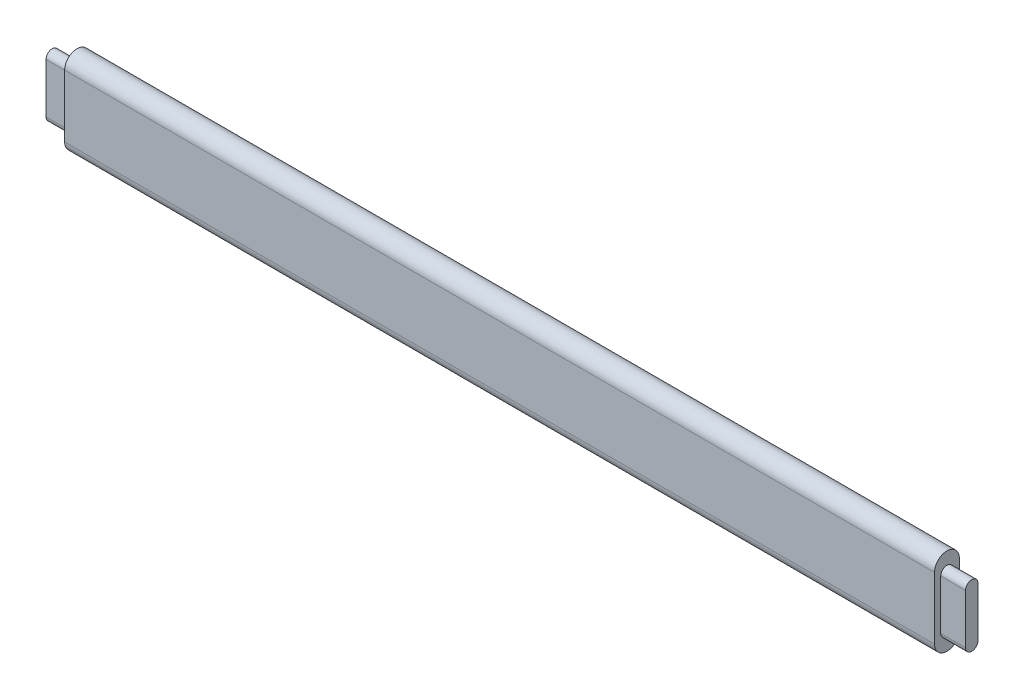
SolidWorks part; units mm, degrees
ref_plane "Front Plane" through (0, 0, 0) normal (0, 0, 1) x (1, 0, 0)
ref_plane "Top Plane" through (0, 0, 0) normal (0, 1, 0) x (1, 0, 0)
ref_plane "Right Plane" through (0, 0, 0) normal (1, 0, 0) x (0, 0, -1)
sketch "Sketch1" plane through (0, 0, 0) normal (1, 0, 0) x (0, 0, -1)
  line L0 (0, 31.75) -> (0, -31.75) construction
  line L1 (12.7, 31.75) -> (12.7, -31.75)
  line L2 (-12.7, 31.75) -> (-12.7, -31.75)
  arc A0 (12.7, 31.75) -> (-12.7, 31.75) centre (0, 31.75) ccw
  arc A1 (-12.7, -31.75) -> (12.7, -31.75) centre (0, -31.75) ccw
  point P3 (0, 0)
  dimension "D1" = 25.4
  dimension "D2" = 63.5
extrude "Boss-Extrude1" add sketch "Sketch1" along normal mid plane 889
sketch "Sketch2" plane through (444.5, 0, 0) normal (1, 0, 0) x (0, 0, -1)
  line L0 (0, -25.4) -> (0, 25.4) construction
  line L1 (-6.35, -25.4) -> (-6.35, 25.4)
  line L2 (6.35, -25.4) -> (6.35, 25.4)
  arc A0 (-6.35, -25.4) -> (6.35, -25.4) centre (0, -25.4) ccw
  arc A1 (6.35, 25.4) -> (-6.35, 25.4) centre (0, 25.4) ccw
  point P2 (0, 0)
  dimension "D2" = 50.8
  dimension "D1" = 12.7
extrude "Boss-Extrude2" add sketch "Sketch2" along normal blind 25.4
mirror "Mirror1" about plane through (0, 0, 0) normal (1, 0, 0) of "Boss-Extrude2"
